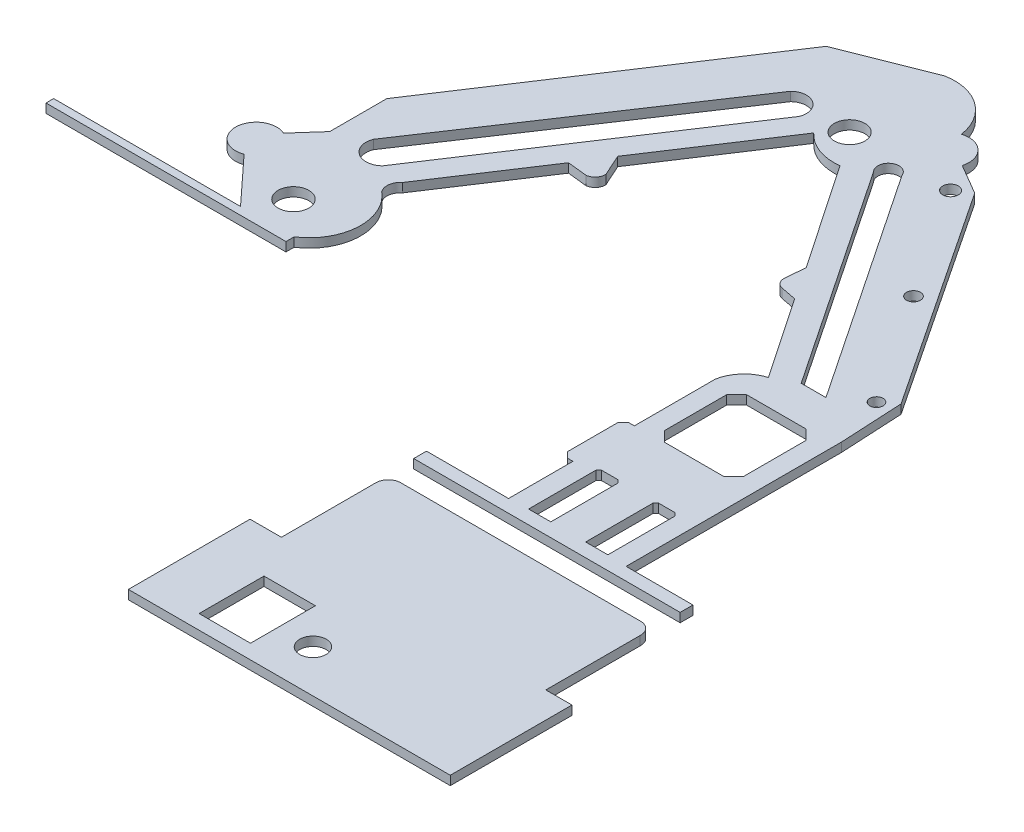
SolidWorks part; units mm, degrees
ref_plane "Front Plane" through (0, 0, 0) normal (0, 0, 1) x (1, 0, 0)
ref_plane "Top Plane" through (0, 0, 0) normal (0, 1, 0) x (1, 0, 0)
ref_plane "Right Plane" through (0, 0, 0) normal (1, 0, 0) x (0, 0, -1)
sketch "Sketch4" plane through (0, 0, 0) normal (0, 1, 0) x (1, 0, 0)
  line L0 (-21.8387, -2.0141) -> (-21.8387, -2.7373)
  line L1 (-21.8387, -2.7373) -> (-8.2676, -2.7373)
  line L2 (-8.2676, -2.7373) -> (-8.2676, -2.2161)
  line L3 (-21.8387, -2.0141) -> (-11.6963, -2.0141)
  line L4 (-11.6963, -2.0141) -> (-13.7992, 0.2608)
  line L5 (-7.9085, 3.3644) -> (-4.3052, 8.8397)
  line L6 (-4.3052, 8.8397) -> (-3.2994, 8.7326)
  line L7 (-2.6398, 9.5154) -> (-3.1553, 10.6573)
  line L8 (-3.1553, 10.6573) -> (0.9992, 16.9702)
  line L9 (3.1991, 16.204) -> (7.0624, 10.5107)
  line L10 (7.0624, 10.5107) -> (6.9865, 9.5293)
  line L11 (7.5124, 8.7543) -> (8.2975, 8.604)
  line L12 (8.2975, 8.604) -> (11.2039, 4.3209)
  line L13 (9.8949, 2.716) -> (9.8949, -1.6332)
  line L14 (9.8949, -1.6332) -> (9.6656, -1.6332)
  line L15 (9.6656, -1.6332) -> (9.2808, -1.9889)
  line L16 (9.2808, -1.9889) -> (9.2808, -4.9128)
  line L17 (9.2808, -4.9128) -> (9.6656, -5.3291)
  line L18 (9.6656, -5.3291) -> (9.8949, -5.3291)
  line L19 (9.8949, -5.3291) -> (9.8949, -8.59)
  line L20 (9.8949, -8.59) -> (5.3575, -8.59)
  line L21 (5.3575, -8.59) -> (5.3575, -9.5985)
  line L22 (5.3575, -9.5985) -> (9.5754, -9.5985)
  line L23 (9.5754, -9.5985) -> (9.5754, -10.8158)
  line L24 (9.5754, -10.8158) -> (6.2672, -10.8158)
  line L25 (5.4714, -11.7099) -> (5.4714, -16.7281)
  line L26 (5.4714, -16.7281) -> (3.7366, -16.7281)
  line L27 (3.7366, -16.7281) -> (3.7366, -23.7561)
  line L28 (3.7366, -23.7561) -> (21.8387, -23.7561)
  line L29 (21.8387, -23.7561) -> (21.8387, -16.7281)
  line L30 (21.8387, -16.7281) -> (20.3942, -16.7281)
  line L31 (20.3942, -16.7281) -> (20.3942, -11.6608)
  line L32 (19.6131, -10.8158) -> (16.9056, -10.8158)
  line L33 (16.9056, -10.8158) -> (16.9056, -9.5985)
  line L34 (16.9056, -9.5985) -> (20.3948, -9.5985)
  line L35 (20.3948, -9.5985) -> (20.3948, -8.59)
  line L36 (20.3948, -8.59) -> (16.697, -8.59)
  line L37 (16.697, -8.59) -> (16.697, 3.1886)
  line L38 (16.697, 3.1886) -> (16.5136, 6.6951)
  line L39 (16.5136, 6.6951) -> (8.4194, 18.8868)
  line L40 (8.4194, 18.8868) -> (6.8135, 19.8279)
  line L41 (1.8101, 23.6992) -> (-2.93, 21.8211)
  line L42 (-2.93, 21.8211) -> (-12.6239, 7.0909)
  line L43 (-12.6239, 7.0909) -> (-12.6239, 3.9472)
  line L44 (-12.6239, 3.9472) -> (-13.7176, 2.716)
  line L45 (-10.8086, 4.6807) -> (-1.5855, 18.4987)
  line L46 (-0.3068, 17.6452) -> (-9.4487, 3.7729)
  line L47 (4.5723, 17.0594) -> (12.6723, 4.9712)
  line L48 (12.6723, 4.9712) -> (13.8003, 4.9712)
  line L49 (13.8003, 4.9712) -> (5.3575, 17.5709)
  line L50 (7.5124, 18.2371) -> (15.6032, 6.0505) construction
  line L51 (9.5754, -10.8158) -> (16.9056, -10.8158)
  line L52 (5.4714, -16.7281) -> (20.3942, -16.7281)
  line L53 (7.0977, -19.3171) -> (9.7412, -19.3171)
  line L54 (7.0977, -19.3171) -> (7.0977, -22.7077)
  line L55 (7.0977, -22.7077) -> (9.7412, -22.7077)
  line L56 (9.7412, -19.3171) -> (9.7412, -22.7077)
  line L57 (7.0977, -19.3171) -> (9.7412, -22.7077) construction
  line L58 (7.0977, -22.7077) -> (9.7412, -19.3171) construction
  line L59 (9.8949, 0.5414) -> (16.697, 0.5414) construction
  line L60 (15.3879, 2.216) -> (14.8879, 2.716)
  line L61 (14.8879, 2.716) -> (11.7039, 2.716)
  line L62 (15.3879, 2.216) -> (15.3879, -1.1332)
  line L63 (14.8879, -1.6332) -> (11.7039, -1.6332)
  line L64 (11.2039, 2.216) -> (11.2039, -1.1332)
  line L65 (15.3879, 2.716) -> (11.2039, -1.6332) construction
  line L66 (15.3879, -1.6332) -> (11.2039, 2.716) construction
  line L67 (11.7039, 2.716) -> (11.2039, 2.216)
  line L68 (11.7039, -1.6332) -> (11.2039, -1.1332)
  line L69 (15.3879, -1.1332) -> (14.8879, -1.6332)
  line L70 (16.697, -8.59) -> (9.8949, -8.59)
  line L71 (16.9056, -9.5985) -> (9.5754, -9.5985)
  line L72 (15.3879, -8.59) -> (15.3879, -5.0128)
  line L73 (15.2879, -4.9128) -> (14.4595, -4.9128)
  line L74 (14.3595, -5.0128) -> (14.3595, -8.59)
  line L75 (13.2959, -1.6332) -> (13.2959, -2.9882) construction
  line L76 (12.2323, -5.0128) -> (12.2323, -8.59)
  line L77 (11.3039, -4.9128) -> (12.1323, -4.9128)
  line L78 (11.2039, -8.59) -> (11.2039, -5.0128)
  line L79 (12.1323, -4.9128) -> (12.2323, -5.0128)
  line L80 (11.2039, -5.0128) -> (11.3039, -4.9128)
  line L81 (14.4595, -4.9128) -> (14.3595, -5.0128)
  line L82 (15.3879, -5.0128) -> (15.2879, -4.9128)
  arc A0 (-8.2676, -2.2161) -> (-8.0417, 2.546) centre (-9.9578, 0.2505) ccw
  arc A1 (-7.9085, 3.3644) -> (-8.0417, 2.546) centre (-7.5659, 2.8886) ccw
  arc A2 (-3.2994, 8.7326) -> (-2.6398, 9.5154) centre (-3.3616, 9.4543) ccw
  arc A3 (0.9992, 16.9702) -> (3.1991, 16.204) centre (2.952, 19.0356) ccw
  arc A4 (6.9865, 9.5293) -> (7.5124, 8.7543) centre (7.6369, 9.4048) ccw
  arc A5 (11.2039, 4.3209) -> (9.8949, 2.716) centre (12.0159, 2.3223) ccw
  arc A6 (6.2672, -10.8158) -> (5.4714, -11.7099) centre (6.3164, -11.6608) ccw
  arc A7 (20.3942, -11.6608) -> (19.6131, -10.8158) centre (19.5812, -11.6288) ccw
  arc A8 (6.8135, 19.8279) -> (5.2417, 21.4134) centre (5.4852, 20.0829) ccw
  arc A9 (5.2417, 21.4134) -> (1.8101, 23.6992) centre (2.383, 20.8405) ccw
  arc A10 (-13.7176, 2.716) -> (-13.7992, 0.2608) centre (-14.1528, 1.5015) ccw
  arc A11 (-10.8086, 4.6807) -> (-9.4487, 3.7729) centre (-10.0219, 4.3867) ccw
  arc A12 (-1.5855, 18.4987) -> (-0.3068, 17.6452) centre (-1.0397, 17.9318) cw
  arc A13 (4.5723, 17.0594) -> (5.3575, 17.5709) centre (4.9019, 17.4118) cw
  circle A14 centre (-10.238, -0.3522) radius 0.2321
  circle A15 centre (-10.238, -0.3522) radius 0.7503
  circle A16 centre (1.9311, 18.2371) radius 0.3438
  circle A17 centre (1.9311, 18.2371) radius 0.7446
  circle A18 centre (7.5124, 18.2371) radius 0.3297
  circle A19 centre (11.5578, 12.1438) radius 0.2839
  circle A20 centre (15.6032, 6.0505) radius 0.2654
  circle A21 centre (11.7412, -21.2536) radius 0.6328
  point P92 (8.4194, -21.0124)
  point P95 (13.2959, 0.5414)
  point P113 (15.3879, -4.9128)
  point P115 (14.3595, -4.9128)
  point P118 (12.2323, -4.9128)
  point P120 (11.2039, -4.9128)
  dimension "D1" = 2
  dimension "D2" = 0.5
  dimension "D3" = 0.5
  dimension "D4" = 0.5
  dimension "D5" = 0.5
  dimension "D6" = 0.5
  dimension "D7" = 0.5
  dimension "D8" = 0.5
  dimension "D9" = 0.5
  dimension "D10" = 0.1
  dimension "D11" = 0.1
  dimension "D12" = 0.1
  dimension "D13" = 0.1
  dimension "D14" = 0.1
  dimension "D15" = 0.1
  dimension "D16" = 0.1
  dimension "D17" = 0.1
extrude "Boss-Extrude1" add sketch "Sketch4" along normal blind 0.5 contours L31 A7 L32 L51 L24 A6 L25 L52 | L52 L26 L27 L28 L29 L30 A21 L53 L56 L55 L54 | L44 A10 L4 L3 L0 L1 L2 A0 A1 L5 L6 A2 L7 L8 A3 L9 L10 A4 L11 L12 A5 L13 L14 L15 L16 L17 L18 L19 L70 L78 L80 L77 L79 L76 L74 L81 L73 L82 L72 L37 L38 L39 L40 A8 A9 L41 L42 L43 | L71 L34 L35 L36 L70 L20 L21 L22
sketch "Sketch5" plane through (0, 0.5, 0) normal (0, 1, 0) x (1, 0, 0)
  line L0 (20.2442, -16.8781) -> (20.2442, -11.6577)
  line L1 (19.61, -10.9658) -> (6.2718, -10.9658)
  line L2 (5.6214, -11.7054) -> (5.6214, -16.8781)
  line L3 (5.6214, -16.8781) -> (3.8866, -16.8781)
  line L4 (3.8866, -16.8781) -> (3.8866, -23.6061)
  line L5 (3.8866, -23.6061) -> (21.6887, -23.6061)
  line L6 (21.6887, -23.6061) -> (21.6887, -16.8781)
  line L7 (21.6887, -16.8781) -> (20.2442, -16.8781)
  line L8 (20.3942, -16.7281) -> (20.3942, -11.6608)
  line L9 (19.6131, -10.8158) -> (6.2672, -10.8158)
  line L10 (5.4714, -11.7099) -> (5.4714, -16.7281)
  line L11 (5.4714, -16.7281) -> (3.7366, -16.7281)
  line L12 (3.7366, -16.7281) -> (3.7366, -23.7561)
  line L13 (3.7366, -23.7561) -> (21.8387, -23.7561)
  line L14 (21.8387, -23.7561) -> (21.8387, -16.7281)
  line L15 (21.8387, -16.7281) -> (20.3942, -16.7281)
  line L16 (20.3942, -16.7281) -> (20.3942, -11.6608)
  line L17 (19.6131, -10.8158) -> (6.2672, -10.8158)
  line L18 (5.4714, -11.7099) -> (5.4714, -16.7281)
  line L19 (5.4714, -16.7281) -> (3.7366, -16.7281)
  line L20 (3.7366, -16.7281) -> (3.7366, -23.7561)
  line L21 (3.7366, -23.7561) -> (21.8387, -23.7561)
  line L22 (21.8387, -23.7561) -> (21.8387, -16.7281)
  line L23 (21.8387, -16.7281) -> (20.3942, -16.7281)
  line L24 (10.0449, -5.1791) -> (10.0449, -8.74)
  line L25 (10.0449, -8.74) -> (5.5075, -8.74)
  line L26 (5.5075, -8.74) -> (5.5075, -9.4485)
  line L27 (5.5075, -9.4485) -> (20.2448, -9.4485)
  line L28 (20.2448, -9.4485) -> (20.2448, -8.74)
  line L29 (20.2448, -8.74) -> (16.547, -8.74)
  line L30 (16.547, -8.74) -> (16.547, 3.1847)
  line L31 (16.547, 3.1847) -> (16.366, 6.6463)
  line L32 (16.366, 6.6463) -> (8.3136, 18.7749)
  line L33 (9.8949, -5.3291) -> (9.8949, -8.59)
  line L34 (9.8949, -8.59) -> (5.3575, -8.59)
  line L35 (5.3575, -8.59) -> (5.3575, -9.5985)
  line L36 (5.3575, -9.5985) -> (20.3948, -9.5985)
  line L37 (20.3948, -9.5985) -> (20.3948, -8.59)
  line L38 (20.3948, -8.59) -> (16.697, -8.59)
  line L39 (16.697, -8.59) -> (16.697, 3.1886)
  line L40 (16.697, 3.1886) -> (16.5136, 6.6951)
  line L41 (16.5136, 6.6951) -> (8.4194, 18.8868)
  line L42 (8.4194, 18.8868) -> (6.8135, 19.8279)
  line L43 (1.8101, 23.6992) -> (-2.93, 21.8211)
  line L44 (-2.93, 21.8211) -> (-12.6239, 7.0909)
  line L45 (-12.6239, 7.0909) -> (-12.6239, 3.9472)
  line L46 (-12.6239, 3.9472) -> (-13.7176, 2.716)
  line L47 (-13.7992, 0.2608) -> (-11.6963, -2.0141)
  line L48 (-11.6963, -2.0141) -> (-21.8387, -2.0141)
  line L49 (-21.8387, -2.0141) -> (-21.8387, -2.7373)
  line L50 (-21.8387, -2.7373) -> (-8.2676, -2.7373)
  line L51 (-8.2676, -2.7373) -> (-8.2676, -2.2161)
  line L52 (-7.9085, 3.3644) -> (-4.3052, 8.8397)
  line L53 (-4.3052, 8.8397) -> (-3.2994, 8.7326)
  line L54 (-2.6398, 9.5154) -> (-3.1553, 10.6573)
  line L55 (-3.1553, 10.6573) -> (0.9992, 16.9702)
  line L56 (3.1991, 16.204) -> (7.0624, 10.5107)
  line L57 (7.0624, 10.5107) -> (6.9865, 9.5293)
  line L58 (7.5124, 8.7543) -> (8.2975, 8.604)
  line L59 (8.2975, 8.604) -> (11.2039, 4.3209)
  line L60 (9.8949, 2.716) -> (9.8949, -1.6332)
  line L61 (9.8949, -1.6332) -> (9.6656, -1.6332)
  line L62 (9.6656, -1.6332) -> (9.2808, -1.9889)
  line L63 (9.2808, -1.9889) -> (9.2808, -4.9128)
  line L64 (9.2808, -4.9128) -> (9.6656, -5.3291)
  line L65 (9.6656, -5.3291) -> (9.8949, -5.3291)
  line L66 (9.8949, -5.3291) -> (9.8949, -8.59)
  line L67 (9.8949, -8.59) -> (5.3575, -8.59)
  line L68 (5.3575, -8.59) -> (5.3575, -9.5985)
  line L69 (5.3575, -9.5985) -> (20.3948, -9.5985)
  line L70 (20.3948, -9.5985) -> (20.3948, -8.59)
  line L71 (20.3948, -8.59) -> (16.697, -8.59)
  line L72 (16.697, -8.59) -> (16.697, 3.1886)
  line L73 (16.697, 3.1886) -> (16.5136, 6.6951)
  line L74 (16.5136, 6.6951) -> (8.4194, 18.8868)
  line L75 (8.4194, 18.8868) -> (6.8135, 19.8279)
  line L76 (1.8101, 23.6992) -> (-2.93, 21.8211)
  line L77 (-2.93, 21.8211) -> (-12.6239, 7.0909)
  line L78 (-12.6239, 7.0909) -> (-12.6239, 3.9472)
  line L79 (-12.6239, 3.9472) -> (-13.7176, 2.716)
  line L80 (-13.7992, 0.2608) -> (-11.6963, -2.0141)
  line L81 (-11.6963, -2.0141) -> (-21.8387, -2.0141)
  line L82 (-21.8387, -2.0141) -> (-21.8387, -2.7373)
  line L83 (-21.8387, -2.7373) -> (-8.2676, -2.7373)
  line L84 (-8.2676, -2.7373) -> (-8.2676, -2.2161)
  line L85 (-7.9085, 3.3644) -> (-4.3052, 8.8397)
  line L86 (-4.3052, 8.8397) -> (-3.2994, 8.7326)
  line L87 (-2.6398, 9.5154) -> (-3.1553, 10.6573)
  line L88 (-3.1553, 10.6573) -> (0.9992, 16.9702)
  line L89 (3.1991, 16.204) -> (7.0624, 10.5107)
  line L90 (7.0624, 10.5107) -> (6.9865, 9.5293)
  line L91 (7.5124, 8.7543) -> (8.2975, 8.604)
  line L92 (8.2975, 8.604) -> (11.2039, 4.3209)
  line L93 (9.8949, 2.716) -> (9.8949, -1.6332)
  line L94 (9.8949, -1.6332) -> (9.6656, -1.6332)
  line L95 (9.6656, -1.6332) -> (9.2808, -1.9889)
  line L96 (9.2808, -1.9889) -> (9.2808, -4.9128)
  line L97 (9.2808, -4.9128) -> (9.6656, -5.3291)
  line L98 (9.6656, -5.3291) -> (9.8949, -5.3291)
  line L99 (8.3136, 18.7749) -> (6.6421, 19.7545)
  line L100 (1.8526, 23.5548) -> (-2.8308, 21.6991)
  line L101 (-2.8308, 21.6991) -> (-12.4739, 7.0459)
  line L102 (-12.4739, 7.0459) -> (-12.4739, 3.8902)
  line L103 (-12.4739, 3.8902) -> (-13.6759, 2.5371)
  line L104 (-13.7544, 0.4332) -> (-11.3533, -2.1641)
  line L105 (-11.3533, -2.1641) -> (-21.6887, -2.1641)
  line L106 (-21.6887, -2.1641) -> (-21.6887, -2.5873)
  line L107 (-21.6887, -2.5873) -> (-8.4176, -2.5873)
  line L108 (-8.4176, -2.5873) -> (-8.4176, -2.1357)
  line L109 (-8.0195, 3.4686) -> (-4.3803, 8.9986)
  line L110 (-4.3803, 8.9986) -> (-3.2987, 8.8834)
  line L111 (-2.7877, 9.4786) -> (-3.326, 10.6708)
  line L112 (-3.326, 10.6708) -> (0.9756, 17.2072)
  line L113 (3.2729, 16.3624) -> (7.216, 10.5514)
  line L114 (7.216, 10.5514) -> (7.1353, 9.5088)
  line L115 (7.5406, 8.9016) -> (8.3868, 8.7396)
  line L116 (8.3868, 8.7396) -> (11.4372, 4.2443)
  line L117 (10.0449, 2.7019) -> (10.0449, -1.7832)
  line L118 (10.0449, -1.7832) -> (9.7243, -1.7832)
  line L119 (9.7243, -1.7832) -> (9.4308, -2.0545)
  line L120 (9.4308, -2.0545) -> (9.4308, -4.8541)
  line L121 (9.4308, -4.8541) -> (9.7312, -5.1791)
  line L122 (9.7312, -5.1791) -> (10.0449, -5.1791)
  arc A0 (20.2442, -11.6577) -> (19.61, -10.9658) centre (19.5812, -11.6288) ccw
  arc A1 (6.2718, -10.9658) -> (5.6214, -11.7054) centre (6.3164, -11.6608) ccw
  arc A2 (20.3942, -11.6608) -> (19.6131, -10.8158) centre (19.5812, -11.6288) ccw
  arc A3 (6.2672, -10.8158) -> (5.4714, -11.7099) centre (6.3164, -11.6608) ccw
  arc A4 (20.3942, -11.6608) -> (19.6131, -10.8158) centre (19.5812, -11.6288) ccw
  arc A5 (6.2672, -10.8158) -> (5.4714, -11.7099) centre (6.3164, -11.6608) ccw
  arc A6 (6.6421, 19.7545) -> (5.1212, 21.2291) centre (5.4852, 20.0829) ccw
  arc A7 (5.1212, 21.2291) -> (1.8526, 23.5548) centre (2.383, 20.8405) ccw
  arc A8 (-13.6759, 2.5371) -> (-13.7544, 0.4332) centre (-14.1528, 1.5015) ccw
  arc A9 (6.8135, 19.8279) -> (5.2417, 21.4134) centre (5.4852, 20.0829) ccw
  arc A10 (5.2417, 21.4134) -> (1.8101, 23.6992) centre (2.383, 20.8405) ccw
  arc A11 (-13.7176, 2.716) -> (-13.7992, 0.2608) centre (-14.1528, 1.5015) ccw
  arc A12 (-8.2676, -2.2161) -> (-8.0417, 2.546) centre (-9.9578, 0.2505) ccw
  arc A13 (-7.9085, 3.3644) -> (-8.0417, 2.546) centre (-7.5659, 2.8886) ccw
  arc A14 (-3.2994, 8.7326) -> (-2.6398, 9.5154) centre (-3.3616, 9.4543) ccw
  arc A15 (0.9992, 16.9702) -> (3.1991, 16.204) centre (2.952, 19.0356) ccw
  arc A16 (6.9865, 9.5293) -> (7.5124, 8.7543) centre (7.6369, 9.4048) ccw
  arc A17 (11.2039, 4.3209) -> (9.8949, 2.716) centre (12.0159, 2.3223) ccw
  arc A18 (6.8135, 19.8279) -> (5.2417, 21.4134) centre (5.4852, 20.0829) ccw
  arc A19 (5.2417, 21.4134) -> (1.8101, 23.6992) centre (2.383, 20.8405) ccw
  arc A20 (-13.7176, 2.716) -> (-13.7992, 0.2608) centre (-14.1528, 1.5015) ccw
  arc A21 (-8.2676, -2.2161) -> (-8.0417, 2.546) centre (-9.9578, 0.2505) ccw
  arc A22 (-7.9085, 3.3644) -> (-8.0417, 2.546) centre (-7.5659, 2.8886) ccw
  arc A23 (-3.2994, 8.7326) -> (-2.6398, 9.5154) centre (-3.3616, 9.4543) ccw
  arc A24 (0.9992, 16.9702) -> (3.1991, 16.204) centre (2.952, 19.0356) ccw
  arc A25 (6.9865, 9.5293) -> (7.5124, 8.7543) centre (7.6369, 9.4048) ccw
  arc A26 (11.2039, 4.3209) -> (9.8949, 2.716) centre (12.0159, 2.3223) ccw
  arc A27 (-8.4176, -2.1357) -> (-8.1514, 2.4421) centre (-9.9578, 0.2505) ccw
  arc A28 (-8.0195, 3.4686) -> (-8.1514, 2.4421) centre (-7.5659, 2.8886) ccw
  arc A29 (-3.2987, 8.8834) -> (-2.7877, 9.4786) centre (-3.3616, 9.4543) ccw
  arc A30 (0.9756, 17.2072) -> (3.2729, 16.3624) centre (2.952, 19.0356) ccw
  arc A31 (7.1353, 9.5088) -> (7.5406, 8.9016) centre (7.6369, 9.4048) ccw
  arc A32 (11.4372, 4.2443) -> (10.0449, 2.7019) centre (12.0159, 2.3223) ccw
  dimension "D1" = 0
  dimension "D2" = 0
  dimension "D3" = 0.15
extrude "Cut-Extrude2" cut sketch "Sketch5" against normal blind 10
sketch "Sketch6" plane through (0, 0.5, 0) normal (0, 1, 0) x (1, 0, 0)
  line L0 (7.0977, -22.7077) -> (9.7412, -22.7077) construction
  line L1 (7.0977, -19.3171) -> (7.0977, -22.7077) construction
  line L2 (7.0977, -19.3171) -> (9.7412, -19.3171) construction
  line L3 (9.7412, -19.3171) -> (9.7412, -22.7077) construction
  line L4 (7.0977, -22.7077) -> (9.7412, -22.7077)
  line L5 (7.0977, -19.3171) -> (7.0977, -22.7077)
  line L6 (7.0977, -19.3171) -> (9.7412, -19.3171)
  line L7 (9.7412, -19.3171) -> (9.7412, -22.7077)
  line L8 (-0.3068, 17.6452) -> (-9.4487, 3.7729) construction
  line L9 (-10.8086, 4.6807) -> (-1.5855, 18.4987) construction
  line L10 (12.6723, 4.9712) -> (13.8003, 4.9712) construction
  line L11 (4.5723, 17.0594) -> (12.6723, 4.9712) construction
  line L12 (13.8003, 4.9712) -> (5.3575, 17.5709) construction
  line L13 (15.3879, -1.1332) -> (14.8879, -1.6332) construction
  line L14 (15.3879, 2.216) -> (14.8879, 2.716) construction
  line L15 (15.3879, 2.216) -> (15.3879, -1.1332) construction
  line L16 (14.8879, -1.6332) -> (11.7039, -1.6332) construction
  line L17 (11.7039, -1.6332) -> (11.2039, -1.1332) construction
  line L18 (11.2039, 2.216) -> (11.2039, -1.1332) construction
  line L19 (11.7039, 2.716) -> (11.2039, 2.216) construction
  line L20 (14.8879, 2.716) -> (11.7039, 2.716) construction
  line L21 (14.4595, -4.9128) -> (14.3595, -5.0128) construction
  line L22 (15.2879, -4.9128) -> (14.4595, -4.9128) construction
  line L23 (15.3879, -5.0128) -> (15.2879, -4.9128) construction
  line L24 (15.3879, -8.59) -> (14.3595, -8.59) construction
  line L25 (15.3879, -8.59) -> (15.3879, -5.0128) construction
  line L26 (14.3595, -5.0128) -> (14.3595, -8.59) construction
  line L27 (12.2323, -8.59) -> (11.2039, -8.59) construction
  line L28 (11.2039, -8.59) -> (11.2039, -5.0128) construction
  line L29 (11.2039, -5.0128) -> (11.3039, -4.9128) construction
  line L30 (11.3039, -4.9128) -> (12.1323, -4.9128) construction
  line L31 (12.1323, -4.9128) -> (12.2323, -5.0128) construction
  line L32 (12.2323, -5.0128) -> (12.2323, -8.59) construction
  line L33 (-0.3068, 17.6452) -> (-9.4487, 3.7729)
  line L34 (-10.8086, 4.6807) -> (-1.5855, 18.4987)
  line L35 (12.6723, 4.9712) -> (13.8003, 4.9712)
  line L36 (4.5723, 17.0594) -> (12.6723, 4.9712)
  line L37 (13.8003, 4.9712) -> (5.3575, 17.5709)
  line L38 (15.3879, -1.1332) -> (14.8879, -1.6332)
  line L39 (15.3879, 2.216) -> (14.8879, 2.716)
  line L40 (15.3879, 2.216) -> (15.3879, -1.1332)
  line L41 (14.8879, -1.6332) -> (11.7039, -1.6332)
  line L42 (11.7039, -1.6332) -> (11.2039, -1.1332)
  line L43 (11.2039, 2.216) -> (11.2039, -1.1332)
  line L44 (11.7039, 2.716) -> (11.2039, 2.216)
  line L45 (14.8879, 2.716) -> (11.7039, 2.716)
  line L46 (14.4595, -4.9128) -> (14.3595, -5.0128)
  line L47 (15.2879, -4.9128) -> (14.4595, -4.9128)
  line L48 (15.3879, -5.0128) -> (15.2879, -4.9128)
  line L49 (15.3879, -8.59) -> (14.3595, -8.59)
  line L50 (15.3879, -8.59) -> (15.3879, -5.0128)
  line L51 (14.3595, -5.0128) -> (14.3595, -8.59)
  line L52 (12.2323, -8.59) -> (11.2039, -8.59)
  line L53 (11.2039, -8.59) -> (11.2039, -5.0128)
  line L54 (11.2039, -5.0128) -> (11.3039, -4.9128)
  line L55 (11.3039, -4.9128) -> (12.1323, -4.9128)
  line L56 (12.1323, -4.9128) -> (12.2323, -5.0128)
  line L57 (12.2323, -5.0128) -> (12.2323, -8.59)
  line L58 (6.9977, -22.8077) -> (9.8412, -22.8077)
  line L59 (9.8412, -19.2171) -> (9.8412, -22.8077)
  line L60 (6.9977, -19.2171) -> (9.8412, -19.2171)
  line L61 (6.9977, -19.2171) -> (6.9977, -22.8077)
  line L62 (-0.2177, 17.5988) -> (-9.3715, 3.7082)
  line L63 (-10.8981, 4.7268) -> (-1.6629, 18.563)
  line L64 (12.619, 4.8712) -> (13.9877, 4.8712)
  line L65 (13.9877, 4.8712) -> (5.4474, 17.6165)
  line L66 (4.4953, 16.9947) -> (12.619, 4.8712)
  line L67 (15.4879, -1.1746) -> (14.9294, -1.7332)
  line L68 (14.9294, -1.7332) -> (11.6625, -1.7332)
  line L69 (11.6625, -1.7332) -> (11.1039, -1.1746)
  line L70 (11.1039, 2.2574) -> (11.1039, -1.1746)
  line L71 (11.6625, 2.816) -> (11.1039, 2.2574)
  line L72 (14.9294, 2.816) -> (11.6625, 2.816)
  line L73 (15.4879, 2.2574) -> (14.9294, 2.816)
  line L74 (15.4879, 2.2574) -> (15.4879, -1.1746)
  line L75 (14.4181, -4.8128) -> (14.2595, -4.9714)
  line L76 (14.2595, -4.9714) -> (14.2595, -8.69)
  line L77 (15.4879, -8.69) -> (14.2595, -8.69)
  line L78 (15.4879, -8.69) -> (15.4879, -4.9714)
  line L79 (15.4879, -4.9714) -> (15.3294, -4.8128)
  line L80 (15.3294, -4.8128) -> (14.4181, -4.8128)
  line L81 (12.3323, -8.69) -> (11.1039, -8.69)
  line L82 (11.1039, -8.69) -> (11.1039, -4.9714)
  line L83 (11.1039, -4.9714) -> (11.2625, -4.8128)
  line L84 (11.2625, -4.8128) -> (12.1738, -4.8128)
  line L85 (12.1738, -4.8128) -> (12.3323, -4.9714)
  line L86 (12.3323, -4.9714) -> (12.3323, -8.69)
  circle A0 centre (11.7412, -21.2536) radius 0.6328 construction
  circle A1 centre (11.7412, -21.2536) radius 0.6328
  circle A2 centre (-10.238, -0.3522) radius 0.7503 construction
  arc A3 (-10.8086, 4.6807) -> (-9.4487, 3.7729) centre (-10.0219, 4.3867) ccw construction
  arc A4 (-0.3068, 17.6452) -> (-1.5855, 18.4987) centre (-1.0397, 17.9318) ccw construction
  circle A5 centre (1.9311, 18.2371) radius 0.7446 construction
  arc A6 (5.3575, 17.5709) -> (4.5723, 17.0594) centre (4.9019, 17.4118) ccw construction
  circle A7 centre (7.5124, 18.2371) radius 0.3297 construction
  circle A8 centre (11.5578, 12.1438) radius 0.2839 construction
  circle A9 centre (15.6032, 6.0505) radius 0.2654 construction
  circle A10 centre (-10.238, -0.3522) radius 0.7503
  arc A11 (-10.8086, 4.6807) -> (-9.4487, 3.7729) centre (-10.0219, 4.3867) ccw
  arc A12 (-0.3068, 17.6452) -> (-1.5855, 18.4987) centre (-1.0397, 17.9318) ccw
  circle A13 centre (1.9311, 18.2371) radius 0.7446
  arc A14 (5.3575, 17.5709) -> (4.5723, 17.0594) centre (4.9019, 17.4118) ccw
  circle A15 centre (7.5124, 18.2371) radius 0.3297
  circle A16 centre (11.5578, 12.1438) radius 0.2839
  circle A17 centre (15.6032, 6.0505) radius 0.2654
  arc A18 (-10.8981, 4.7268) -> (-9.3715, 3.7082) centre (-10.0219, 4.3867) ccw
  arc A19 (-0.2177, 17.5988) -> (-1.6629, 18.563) centre (-1.0397, 17.9318) ccw
  arc A20 (5.4474, 17.6165) -> (4.4953, 16.9947) centre (4.9019, 17.4118) ccw
  circle A21 centre (11.7412, -21.2536) radius 0.7328
  circle A22 centre (-10.238, -0.3522) radius 0.8503
  circle A23 centre (1.9311, 18.2371) radius 0.8446
  circle A24 centre (7.5124, 18.2371) radius 0.4297
  circle A25 centre (11.5578, 12.1438) radius 0.3839
  circle A26 centre (15.6032, 6.0505) radius 0.3654
  dimension "D1" = 0.1
extrude "Cut-Extrude3" cut sketch "Sketch6" against normal blind 10
